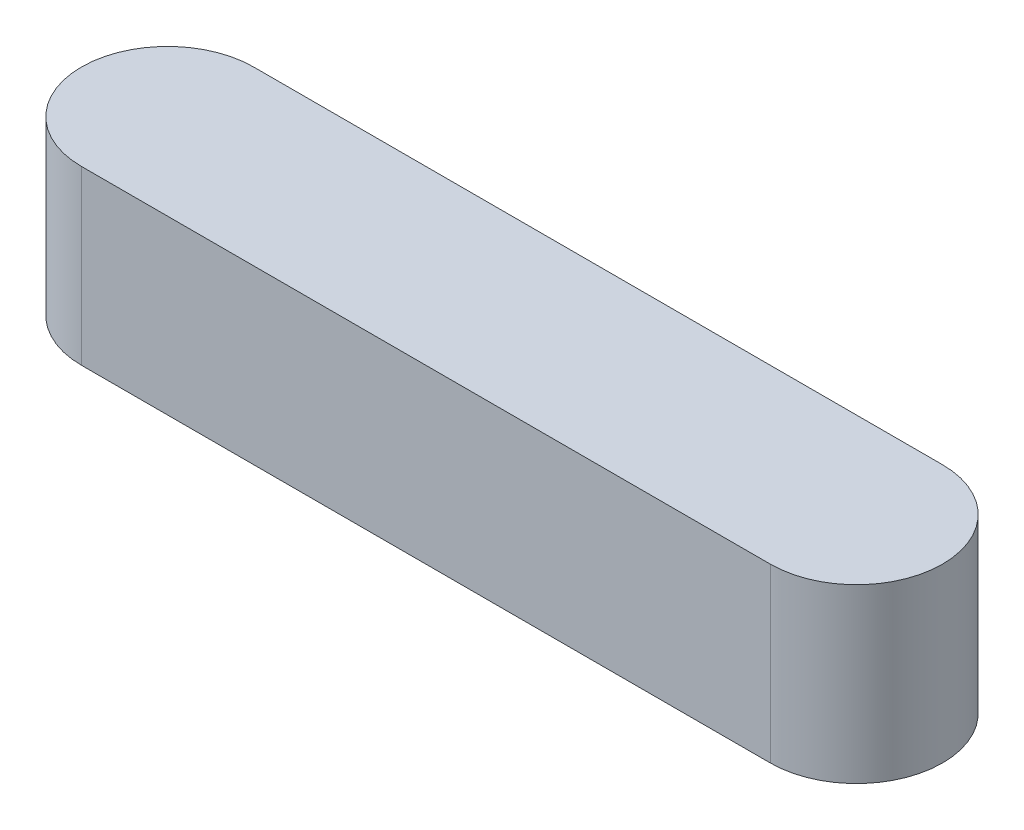
SolidWorks part; units mm, degrees
ref_plane "Ön Düzlem" through (0, 0, 0) normal (0, 0, 1) x (1, 0, 0)
ref_plane "Üst Düzlem" through (0, 0, 0) normal (0, 1, 0) x (1, 0, 0)
ref_plane "Sağ Düzlem" through (0, 0, 0) normal (1, 0, 0) x (0, 0, -1)
sketch "Çizim1" plane through (0, 0, 0) normal (0, 1, 0) x (1, 0, 0)
  line L0 (-93.3804, 0) -> (106.6196, 0) construction
  line L1 (-93.3804, 25) -> (106.6196, 25)
  line L2 (-93.3804, -25) -> (106.6196, -25)
  arc A0 (-93.3804, 25) -> (-93.3804, -25) centre (-93.3804, 0) ccw
  arc A1 (106.6196, -25) -> (106.6196, 25) centre (106.6196, 0) ccw
  point P3 (6.6196, 0)
  dimension "D2" = 25
  dimension "D1" = 200
extrude "Yükseklik-Ekstrüzyon1" add sketch "Çizim1" along normal blind 50
